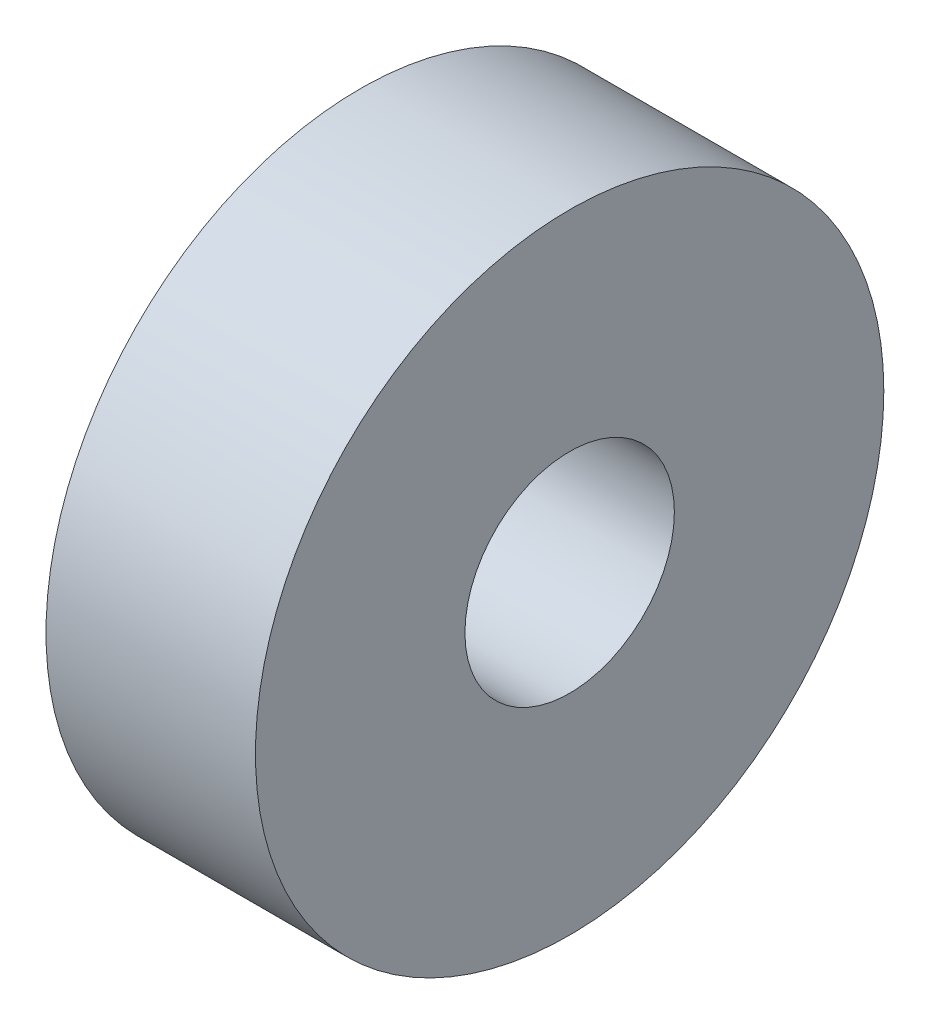
SolidWorks part; units mm, degrees
ref_plane "前视基准面" through (0, 0, 0) normal (0, 0, 1) x (1, 0, 0)
ref_plane "上视基准面" through (0, 0, 0) normal (0, 1, 0) x (1, 0, 0)
ref_plane "右视基准面" through (0, 0, 0) normal (1, 0, 0) x (0, 0, -1)
other "Configuration Table"
sketch "草图1" plane through (0, 0, 0) normal (1, 0, 0) x (0, 0, -1)
  circle A0 centre (0, 0) radius 2
  circle A1 centre (0, 0) radius 6
  dimension "D1" = 12
  dimension "D2" = 4
extrude "凸台-拉伸1" add sketch "草图1" along normal blind 4
